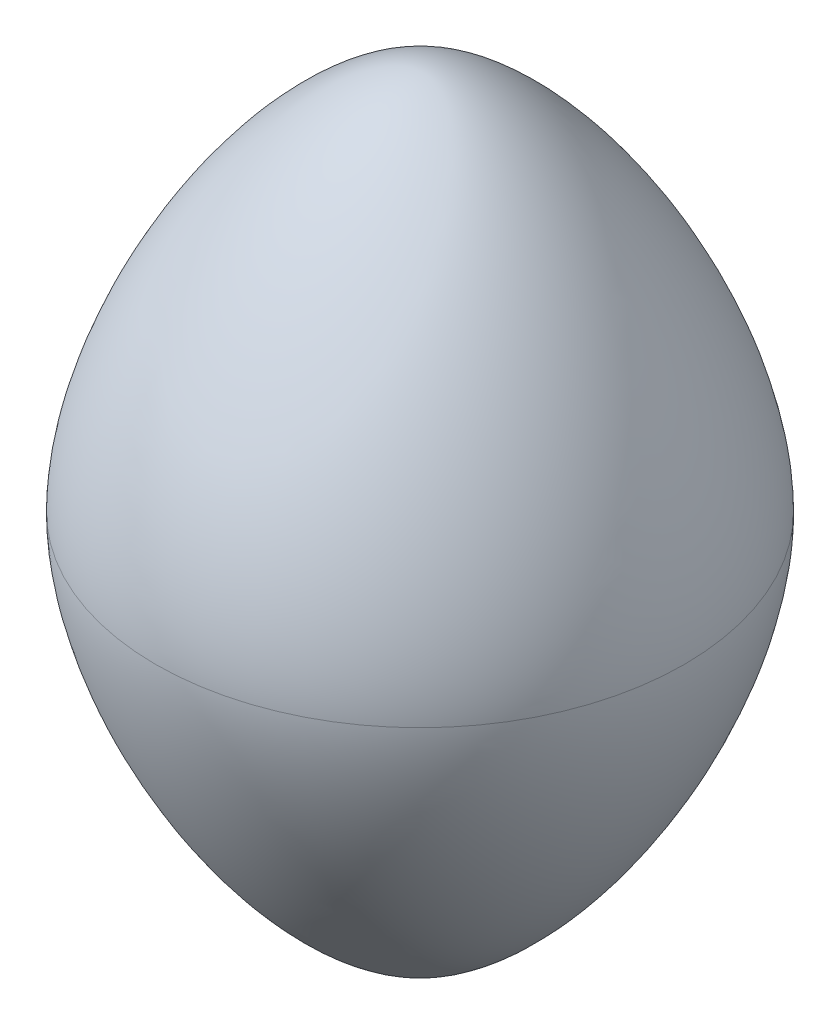
SolidWorks part; units mm, degrees
ref_plane "Front Plane" through (0, 0, 0) normal (0, 0, 1) x (1, 0, 0)
ref_plane "Top Plane" through (0, 0, 0) normal (0, 1, 0) x (1, 0, 0)
ref_plane "Right Plane" through (0, 0, 0) normal (1, 0, 0) x (0, 0, -1)
sketch "Sketch1" plane through (0, 0, 0) normal (0, 0, 1) x (1, 0, 0)
  line L1 (0, 31) -> (0, -31)
  line L6 (0, 31) -> (21.5, 31) construction
  line L7 (0, 0) -> (21.5, 0) construction
  line L14 (21.5, 0) -> (21.5, 31) construction
  conic Q0 (0, 31) -> (21.5, 0) control (21.5, 31) rho 0.3
  conic Q1 (0, -31) -> (21.5, 0) control (21.5, -31) rho 0.3
  dimension "Egg Height/2" = 31
  dimension "egg max radius" = 21.5
revolve "Revolve1" add sketch "Sketch1" angle 360 about L1
